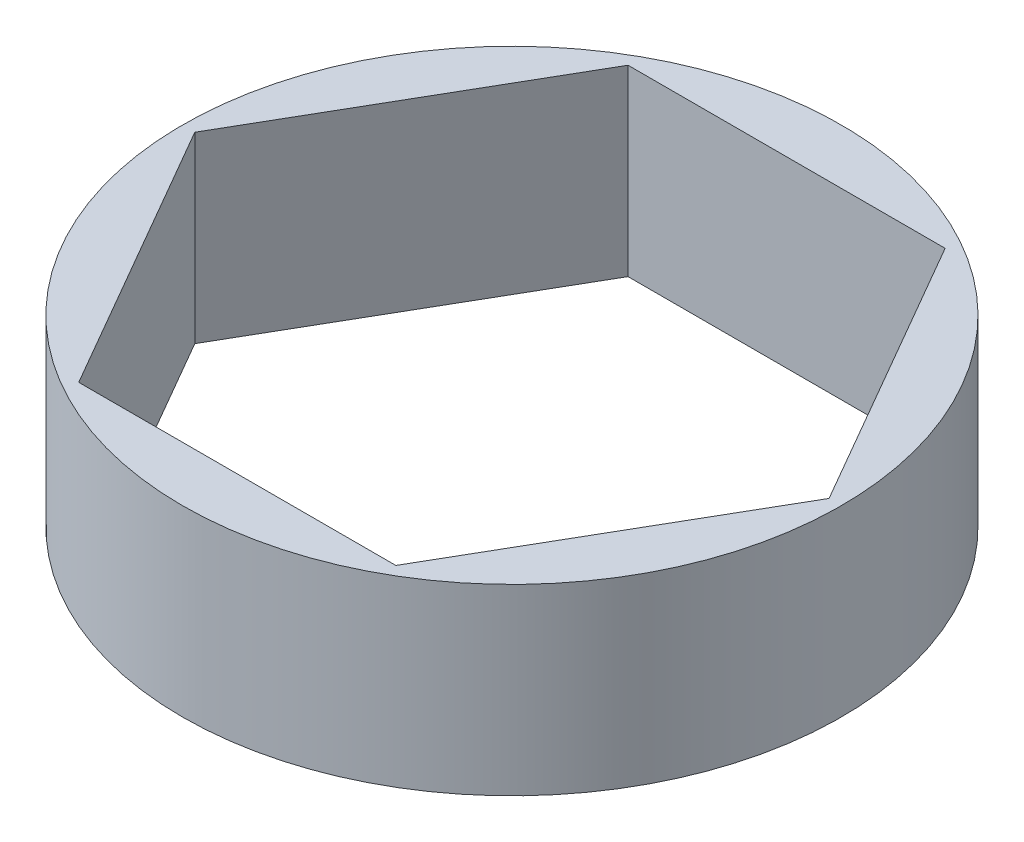
SolidWorks part; units mm, degrees
ref_plane "Front Plane" through (0, 0, 0) normal (0, 0, 1) x (1, 0, 0)
ref_plane "Top Plane" through (0, 0, 0) normal (0, 1, 0) x (1, 0, 0)
ref_plane "Right Plane" through (0, 0, 0) normal (1, 0, 0) x (0, 0, -1)
sketch "Sketch1" plane through (0, 0, 0) normal (0, 1, 0) x (1, 0, 0)
  line L0 (0, 0) -> (35.7746, 0) construction
  line L1 (8.6603, 0) -> (4.3301, 7.5)
  line L2 (4.3301, 7.5) -> (-4.3301, 7.5)
  line L3 (-4.3301, 7.5) -> (-8.6603, 0)
  line L4 (-8.6603, 0) -> (-4.3301, -7.5)
  line L5 (-4.3301, -7.5) -> (4.3301, -7.5)
  line L6 (4.3301, -7.5) -> (8.6603, 0)
  circle A0 centre (0, 0) radius 7.5 construction
  circle A1 centre (0, 0) radius 9
  dimension "D1" = 15
  dimension "D2" = 18
extrude "Boss-Extrude1" add sketch "Sketch1" along normal blind 5
